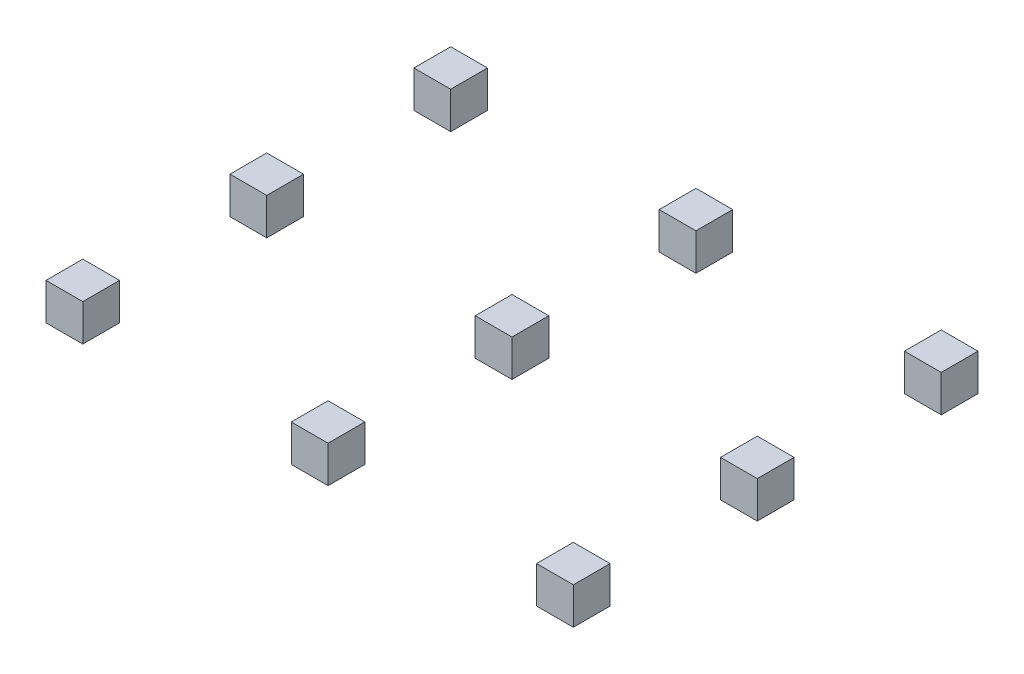
SolidWorks part; units mm, degrees
ref_plane "Спереди" through (0, 0, 0) normal (0, 0, 1) x (1, 0, 0)
ref_plane "Сверху" through (0, 0, 0) normal (0, 1, 0) x (1, 0, 0)
ref_plane "Справа" through (0, 0, 0) normal (1, 0, 0) x (0, 0, -1)
sketch "Эскиз1" plane through (0, 0, 0) normal (0, 1, 0) x (1, 0, 0)
  line L0 (0, 0) -> (-390667.6747, 0) construction
  line L1 (0, 0) -> (0, 390667.6747) construction
  line L2 (-150, -1350) -> (150, -1350)
  line L3 (-2150, -1350) -> (-1850, -1350)
  line L4 (-2150, -1350) -> (-2150, -1650)
  line L5 (-2150, -1650) -> (-1850, -1650)
  line L6 (-1850, -1350) -> (-1850, -1650)
  line L7 (-2150, -1350) -> (-1850, -1650) construction
  line L8 (-2150, -1650) -> (-1850, -1350) construction
  line L9 (-150, -1350) -> (-150, -1650)
  line L10 (150, -1350) -> (150, -1650)
  line L11 (-150, -1650) -> (150, -1650)
  line L12 (1850, -1350) -> (2150, -1350)
  line L13 (1850, -1350) -> (1850, -1650)
  line L14 (2150, -1350) -> (2150, -1650)
  line L15 (1850, -1650) -> (2150, -1650)
  line L16 (-150, 150) -> (150, 150)
  line L17 (-150, 150) -> (-150, -150)
  line L18 (150, 150) -> (150, -150)
  line L19 (-150, -150) -> (150, -150)
  line L20 (1850, 150) -> (2150, 150)
  line L21 (1850, 150) -> (1850, -150)
  line L22 (2150, 150) -> (2150, -150)
  line L23 (1850, -150) -> (2150, -150)
  line L24 (-150, 1650) -> (150, 1650)
  line L25 (-150, 1650) -> (-150, 1350)
  line L26 (150, 1650) -> (150, 1350)
  line L27 (-150, 1350) -> (150, 1350)
  line L28 (1850, 1650) -> (2150, 1650)
  line L29 (1850, 1650) -> (1850, 1350)
  line L30 (2150, 1650) -> (2150, 1350)
  line L31 (1850, 1350) -> (2150, 1350)
  line L32 (-2150, 150) -> (-1850, 150)
  line L33 (-2150, 150) -> (-2150, -150)
  line L34 (-1850, 150) -> (-1850, -150)
  line L35 (-2150, -150) -> (-1850, -150)
  line L36 (-2150, 1650) -> (-1850, 1650)
  line L37 (-2150, 1650) -> (-2150, 1350)
  line L38 (-1850, 1650) -> (-1850, 1350)
  line L39 (-2150, 1350) -> (-1850, 1350)
  point P5 (-2000, -1500)
  dimension "D1" = 300
  dimension "D2" = 300
  dimension "D3" = 2000
  dimension "D4" = 1500
  dimension "D5" = 3
  dimension "D6" = 3
extrude "Бобышка-Вытянуть1" add sketch "Эскиз1" along normal blind 300
